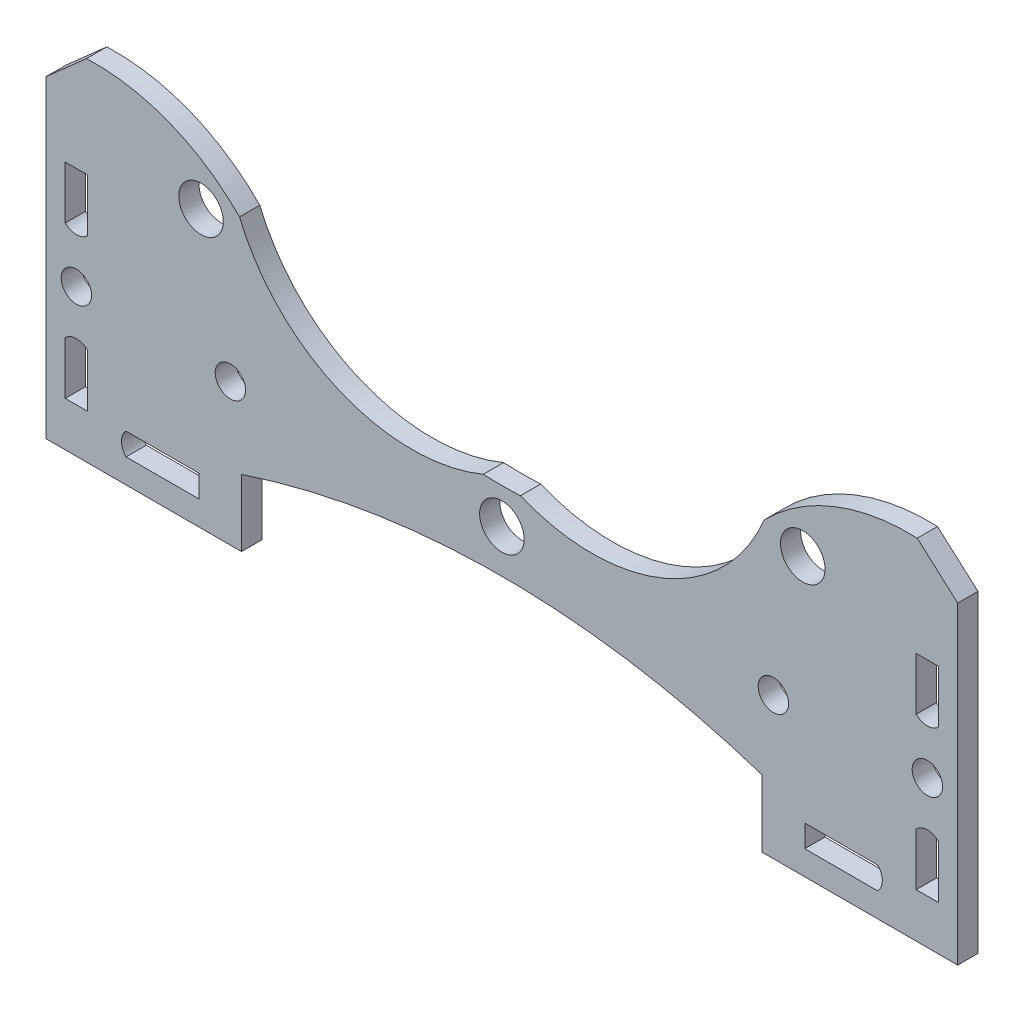
SolidWorks part; units mm, degrees
ref_plane "前视基准面" through (0, 0, 0) normal (0, 0, 1) x (1, 0, 0)
ref_plane "上视基准面" through (0, 0, 0) normal (0, 1, 0) x (1, 0, 0)
ref_plane "右视基准面" through (0, 0, 0) normal (1, 0, 0) x (0, 0, -1)
sketch "草图3" plane through (0, 0, 0) normal (0, 0, 1) x (1, 0, 0)
  line L0 (-37, -1.9902) -> (-37, -2.0902) construction
  line L2 (-41, -4.4902) -> (-42, -4.4902)
  line L4 (41, -4.4902) -> (45, -4.4902)
  line L5 (-37, 0.0098) -> (-30, 0.0098) construction
  line L6 (-37, 0.0098) -> (-37, -1.9902) construction
  line L7 (-37, -1.9902) -> (-30, -1.9902) construction
  line L8 (-30, 0.0098) -> (-30, -1.9902) construction
  line L9 (-37, -2.0902) -> (-37.1, -2.0902) construction
  line L11 (30, 0.0098) -> (37, 0.0098) construction
  line L12 (30, 0.0098) -> (30, -1.9902) construction
  line L13 (30, -1.9902) -> (37, -1.9902) construction
  line L14 (37, 0.0098) -> (37, -1.9902) construction
  line L19 (-37.1, -2.0902) -> (-29.9, -2.0902)
  line L21 (-37.1, 0.1098) -> (-29.9, 0.1098)
  line L22 (-29.9, -2.0902) -> (-29.9, 0.1098)
  line L23 (29.9, -2.0902) -> (29.9, 0.1098)
  line L24 (37.1, -2.0902) -> (29.9, -2.0902)
  line L26 (37.1, 0.1098) -> (29.9, 0.1098)
  line L34 (-25.7, -4.4902) -> (-25.7, -0.3902)
  line L39 (-41, 0.0098) -> (-44, 0.0098) construction
  line L40 (-44, 0.0098) -> (-44, 5.0098) construction
  line L41 (-44, 5.0098) -> (-41, 5.0098) construction
  line L55 (-41, 15.0098) -> (-44, 15.0098) construction
  line L56 (-44, 15.0098) -> (-44, 20.0098) construction
  line L57 (-44, 20.0098) -> (-41, 20.0098) construction
  line L79 (-41, -4.4902) -> (-25.7, -4.4902)
  line L82 (0, 10.5098) -> (0, 5.0098) construction
  line L87 (-25.7, -0.3902) -> (-25.7, 2.1098)
  line L88 (41, -4.4902) -> (25.7, -4.4902)
  line L89 (25.7, -0.3902) -> (25.7, 2.1098)
  line L90 (25.7, -4.4902) -> (25.7, -0.3902)
  line L97 (-42, 0.0098) -> (-42, 5.0098) construction
  line L98 (-42, 15.0098) -> (-42, 20.0098) construction
  line L100 (-43.1, 5.1098) -> (-43.1, -0.0902)
  line L101 (-43.1, -0.0902) -> (-40.9, -0.0902)
  line L102 (-40.9, 5.1098) -> (-40.9, -0.0902)
  line L103 (-43.1, 5.1098) -> (-40.9, -0.0902) construction
  line L104 (-43.1, -0.0902) -> (-40.9, 5.1098) construction
  line L106 (-43.1, 20.1098) -> (-40.9, 20.1098)
  line L107 (-43.1, 20.1098) -> (-43.1, 14.9098)
  line L109 (-40.9, 20.1098) -> (-40.9, 14.9098)
  line L110 (-43.1, 20.1098) -> (-40.9, 14.9098) construction
  line L111 (-43.1, 14.9098) -> (-40.9, 20.1098) construction
  line L114 (43.1, 14.9098) -> (40.9, 20.1098) construction
  line L115 (43.1, 20.1098) -> (40.9, 14.9098) construction
  line L116 (43.1, -0.0902) -> (40.9, 5.1098) construction
  line L117 (43.1, 5.1098) -> (40.9, -0.0902) construction
  line L118 (42, 15.0098) -> (42, 20.0098) construction
  line L119 (42, 0.0098) -> (42, 5.0098) construction
  line L120 (44, 20.0098) -> (41, 20.0098) construction
  line L121 (44, 15.0098) -> (44, 20.0098) construction
  line L122 (41, 15.0098) -> (44, 15.0098) construction
  line L123 (44, 5.0098) -> (41, 5.0098) construction
  line L124 (44, 0.0098) -> (44, 5.0098) construction
  line L125 (41, 0.0098) -> (44, 0.0098) construction
  line L126 (40.9, 20.1098) -> (40.9, 14.9098)
  line L128 (43.1, 20.1098) -> (43.1, 14.9098)
  line L129 (43.1, 20.1098) -> (40.9, 20.1098)
  line L130 (40.9, 5.1098) -> (40.9, -0.0902)
  line L131 (43.1, -0.0902) -> (40.9, -0.0902)
  line L132 (43.1, 5.1098) -> (43.1, -0.0902)
  line L134 (-42, -4.4902) -> (-44, -4.4902)
  line L135 (-44, -4.4902) -> (-45, -4.4902)
  line L137 (41, 30.0098) -> (45, 26.4631)
  line L140 (-45, 14.5098) -> (-45, 4.5098)
  line L141 (45, 14.5098) -> (45, 4.5098)
  line L142 (0, 10.5098) -> (0, 52.5098) construction
  line L143 (-44, 5.0098) -> (-44, 15.0098) construction
  line L144 (-44, 10.0098) -> (-49.7747, 10.0098) construction
  line L145 (-45, -4.4902) -> (-45, 4.5098)
  line L147 (45, 26.4631) -> (45, 14.5098)
  line L148 (45, 4.5098) -> (45, -4.4902)
  line L149 (-45, 26.4631) -> (-45, 14.5098)
  line L150 (-41, 30.0098) -> (-45, 26.4631)
  circle A4 centre (0, 10.5098) radius 2.2
  circle A13 centre (-29.6985, 22.8113) radius 2.2
  circle A14 centre (-42, 52.5098) radius 2 construction
  circle A17 centre (-26.8, 9.5098) radius 1.5
  circle A18 centre (26.8, 9.5098) radius 1.5
  arc A19 (37.1, 0.1098) -> (37.1, -2.0902) centre (36, -0.9902) cw
  arc A20 (-37.1, -2.0902) -> (-37.1, 0.1098) centre (-36, -0.9902) cw
  arc A21 (-43.1, 5.1098) -> (-40.9, 5.1098) centre (-42, 4.0098) cw
  arc A22 (-43.1, 14.9098) -> (-40.9, 14.9098) centre (-42, 16.0098) ccw
  arc A23 (40.9, 14.9098) -> (43.1, 14.9098) centre (42, 16.0098) ccw
  arc A24 (40.9, 5.1098) -> (43.1, 5.1098) centre (42, 4.0098) cw
  circle A25 centre (0, 52.5098) radius 42 construction
  circle A26 centre (-42, 10.0098) radius 1.5
  circle A29 centre (42, 10.0098) radius 1.5
  circle A32 centre (29.6985, 22.8113) radius 2.2
  circle A43 centre (0, 52.5098) radius 38.5 construction
  arc A44 (-25.8968, 24.021) -> (-1.8313, 14.0534) centre (-8.8802, 31.0699) ccw
  arc A45 (-41, 30.0098) -> (-25.8968, 24.021) centre (-40.1688, 10.0668) cw
  arc A46 (41, 30.0098) -> (25.8968, 24.021) centre (40.1688, 10.0668) ccw
  arc A47 (25.8968, 24.021) -> (1.8313, 14.0534) centre (8.8802, 31.0699) cw
  arc A48 (-1.8313, 14.0534) -> (1.8313, 14.0534) centre (0, 52.5098) ccw
  arc A50 (-25.7, 2.1098) -> (25.7, 2.1098) centre (0, -75.4652) cw
  point P39 (-42, 2.5098)
  point P55 (-42, 17.5098)
  point P90 (42, 17.5098)
  point P91 (42, 2.5098)
extrude "凸台-拉伸1" add sketch "草图3" along normal blind 2
